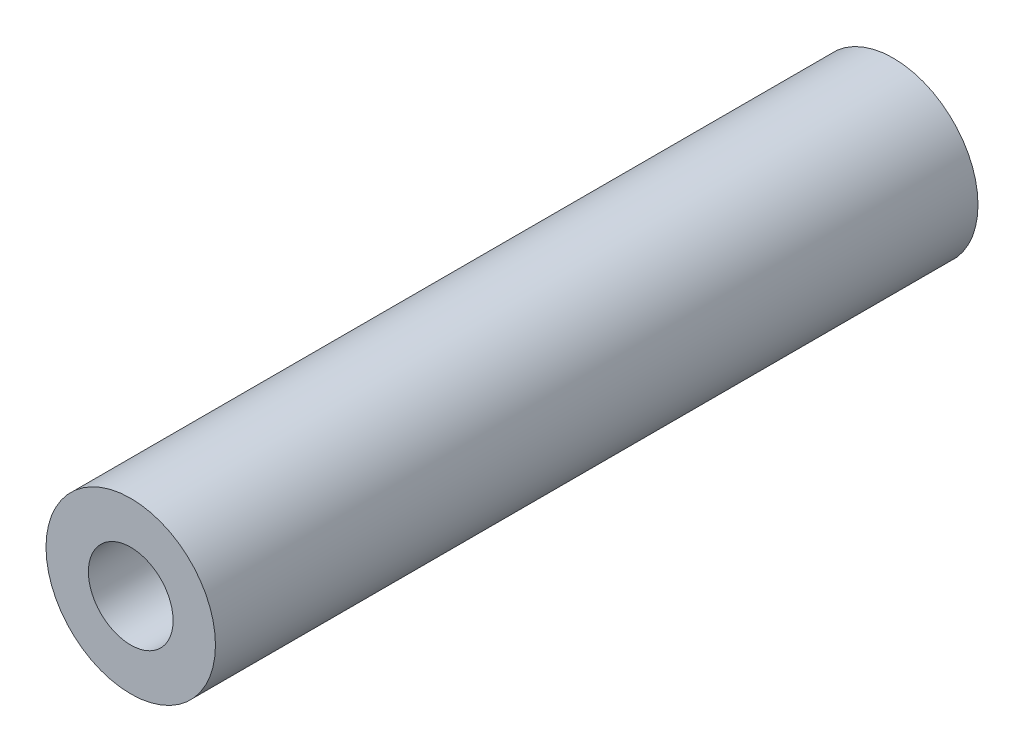
SolidWorks part; units mm, degrees
ref_plane "Front Plane" through (0, 0, 0) normal (0, 0, 1) x (1, 0, 0)
ref_plane "Top Plane" through (0, 0, 0) normal (0, 1, 0) x (1, 0, 0)
ref_plane "Right Plane" through (0, 0, 0) normal (1, 0, 0) x (0, 0, -1)
sketch "Sketch1" plane through (0, 0, 0) normal (0, 0, 1) x (1, 0, 0)
  circle A0 centre (0, 0) radius 12.7
  circle A1 centre (0, 0) radius 25.4
  dimension "D1" = 25.4
  dimension "D2" = 50.8
extrude "Boss-Extrude1" add sketch "Sketch1" along normal blind 228.6
